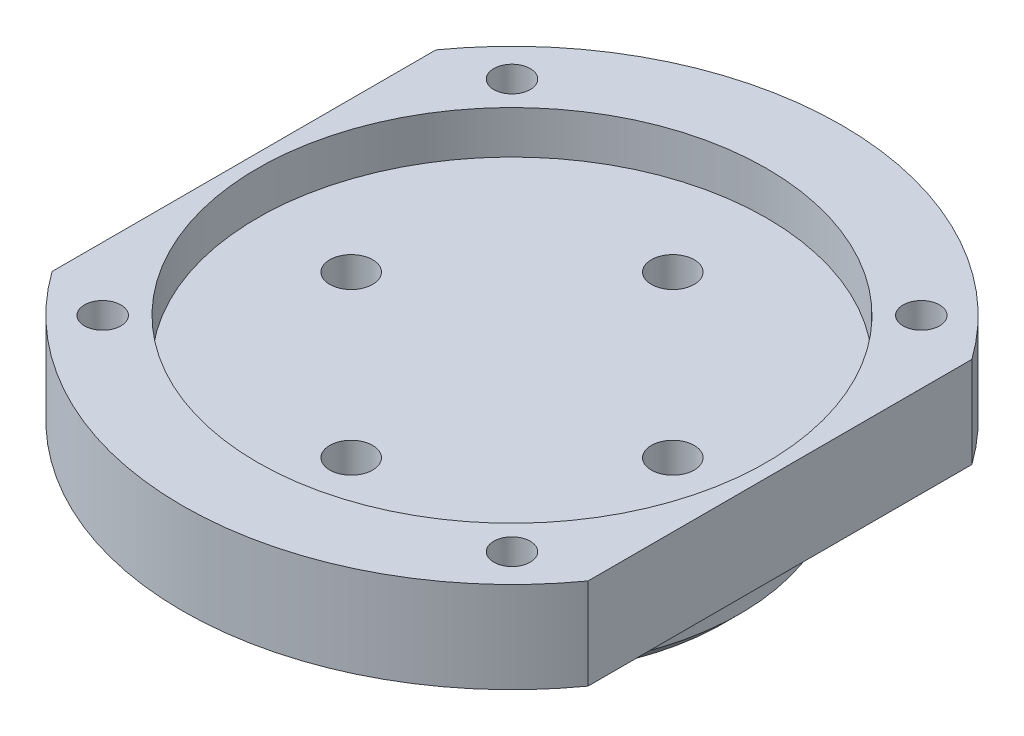
SolidWorks part; units mm, degrees
ref_plane "Front Plane" through (0, 0, 0) normal (0, 0, 1) x (1, 0, 0)
ref_plane "Top Plane" through (0, 0, 0) normal (0, 1, 0) x (1, 0, 0)
ref_plane "Right Plane" through (0, 0, 0) normal (1, 0, 0) x (0, 0, -1)
sketch "Sketch1" plane through (0, 0, 0) normal (0, 0, 1) x (1, 0, 0)
  line L0 (42.5, 0) -> (42.5, 13)
  line L1 (42.5, 13) -> (61.5, 13)
  line L2 (61.5, 13) -> (61.5, 30)
  line L3 (61.5, 30) -> (47.5, 30)
  line L4 (0, 22) -> (0, 0)
  line L5 (0, 0) -> (42.5, 0)
  line L6 (0, 0) -> (0, 58.2535) construction
  line L7 (47.5, 30) -> (47.5, 22)
  line L8 (47.5, 22) -> (0, 22)
  dimension "D1" = 85
  dimension "D2" = 123
  dimension "D3" = 13
  dimension "D4" = 17
  dimension "D5" = 95
  dimension "D6" = 8
revolve "Revolve1" add sketch "Sketch1" angle 360 about L6
sketch "Sketch2" plane through (0, 0, 0) normal (0, -1, 0) x (1, 0, 0)
  circle A0 centre (0, 0) radius 30 construction
  circle A1 centre (30, 0) radius 4
  circle A2 centre (0, -30) radius 4
  circle A3 centre (-30, 0) radius 4
  circle A4 centre (0, 30) radius 4
  point P14 (0, 0)
  dimension "D1" = 60
  dimension "D2" = 8
  dimension "D3" = 4
sketch "Sketch4" plane through (0, 30, 0) normal (0, 1, 0) x (1, 0, 0)
  line L1 (-50, -61.5) -> (50, -61.5)
  line L2 (-50, -61.5) -> (-50, 61.5)
  line L3 (-50, 61.5) -> (50, 61.5)
  line L4 (50, -61.5) -> (50, 61.5)
  line L5 (-50, -61.5) -> (50, 61.5) construction
  line L6 (-50, 61.5) -> (50, -61.5) construction
  circle A0 centre (0, 0) radius 61.5 construction
  point P0 (0, 0)
  dimension "D1" = 100
extrude "Cut-Extrude3" cut sketch "Sketch4" against normal up to next flip side to cut
sketch "Sketch5" plane through (0, 30, 0) normal (0, 1, 0) x (1, 0, 0)
  line L0 (0, 0) -> (-38.1838, 38.1838) construction
  line L5 (0, 0) -> (0, 47.5) construction
  circle A0 centre (0, 0) radius 54 construction
  circle A1 centre (-38.1838, 38.1838) radius 2.5
  circle A2 centre (38.1838, 38.1838) radius 2.5
  circle A3 centre (38.1838, -38.1838) radius 2.5
  circle A4 centre (-38.1838, -38.1838) radius 2.5
  circle A5 centre (0, 0) radius 47.5 construction
  point P17 (0, 0)
  dimension "D1" = 108
  dimension "D2" = 5
  dimension "D4" = 45
  dimension "D3" = 4
extrude "Cut-Extrude4" cut sketch "Sketch5" against normal up to next
extrude "Cut-Extrude5" cut sketch "Sketch2" against normal through all
sketch "Sketch6" plane through (0, 0, 0) normal (0, -1, 0) x (1, 0, 0)
  circle A8 centre (0, 30) radius 8
  circle A9 centre (30, 0) radius 8
  circle A10 centre (-30, 0) radius 8
  circle A11 centre (0, -30) radius 8
  dimension "D1" = 16
extrude "Cut-Extrude6" cut sketch "Sketch6" against normal blind 13
chamfer "Chamfer1" distance 3 angle 45 1 edges at (0, 0, -42.5)
hole_wizard "M8 Tapped Hole1" positions "3DSketch1" profile "Sketch7" tap size "M8" standard "ISO"
sketch3d "3DSketch1"
  line L0 (38.1838, 13, -38.1838) -> (38.1838, 30, -38.1838) construction
  line L1 (-38.1838, 13, -38.1838) -> (-38.1838, 30, -38.1838) construction
  line L2 (-38.1838, 13, 38.1838) -> (-38.1838, 30, 38.1838) construction
  line L3 (38.1838, 13, 38.1838) -> (38.1838, 30, 38.1838) construction
  point P0 (38.1838, 13, -38.1838)
  point P4 (-38.1838, 13, -38.1838)
  point P8 (-38.1838, 13, 38.1838)
  point P12 (38.1838, 13, 38.1838)
sketch "Sketch7" plane through (38.1838, 13, -38.1838) normal (1, 0, 0) x (0, 0, -1)
  line L0 (0, 0) -> (0, 21.7929)
  line L1 (0, 21.7929) -> (3.4, 19.75)
  line L2 (3.4, 19.75) -> (3.4, 0.625)
  line L3 (3.4, 0.625) -> (4.025, 0)
  line L5 (4.025, 0) -> (0, 0)
  line L6 (-3.4, 0.625) -> (-4.025, 0) construction
  line L10 (0, 21.7929) -> (-3.4, 19.75) construction
  line L11 (0, -6.35) -> (0, 107.95) construction
  dimension "Tap Drill Dia." = 6.8
  dimension "Tap Drill Depth" = 19.75
  dimension "Near C'Sink Dia." = 8.05
  dimension "Near C'Sink Angle" = 90
  dimension "Drill Angle" = 118
cosmetic thread "Hole Thread5" parameters "D1"=16, "D2"=8
cosmetic thread "Hole Thread6" parameters "D1"=16, "D2"=8
cosmetic thread "Hole Thread7" parameters "D1"=16, "D2"=8
cosmetic thread "Hole Thread8" parameters "D1"=16, "D2"=8
